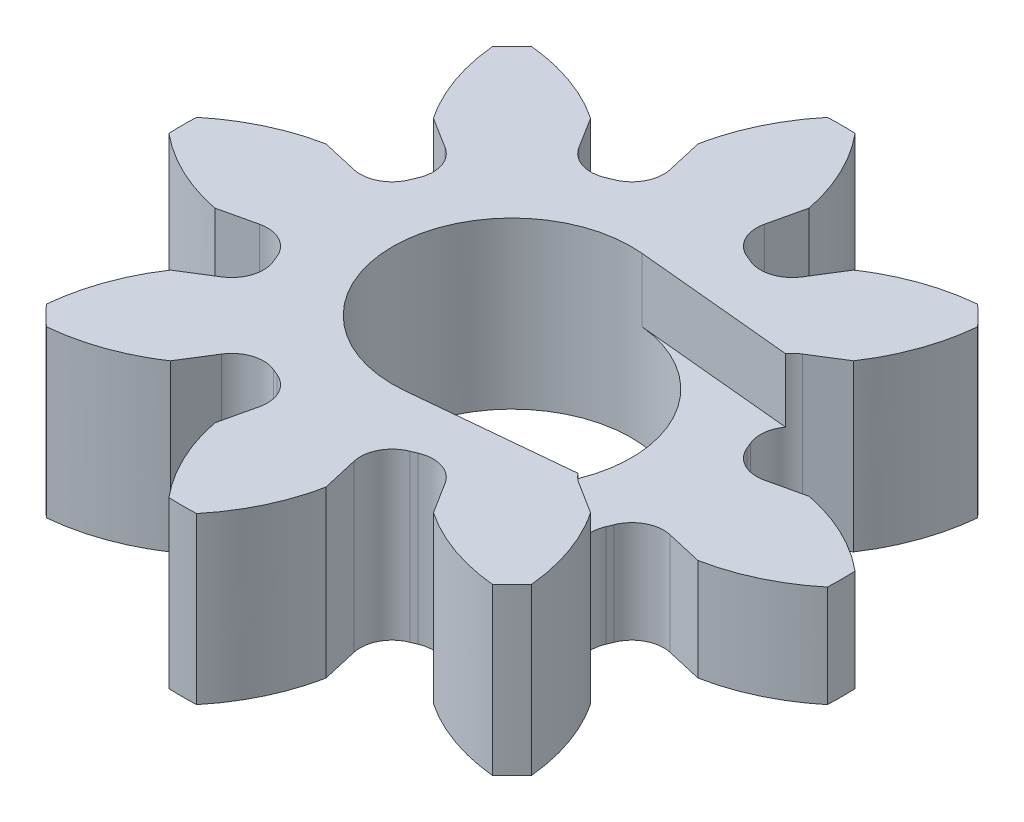
SolidWorks part; units mm, degrees
ref_plane "Front Plane" through (0, 0, 0) normal (0, 0, 1) x (1, 0, 0)
ref_plane "Top Plane" through (0, 0, 0) normal (0, 1, 0) x (1, 0, 0)
ref_plane "Right Plane" through (0, 0, 0) normal (1, 0, 0) x (0, 0, -1)
sketch "Sketch1" plane through (0, 0, 0) normal (0, 1, 0) x (1, 0, 0)
  circle A0 centre (0, 0) radius 8.283 construction
  circle A1 centre (0, 0) radius 5.6945
  circle A2 centre (0, 0) radius 3.75
  dimension "D1" = 16.566
  dimension "D2" = 11.389
  dimension "D3" = 7.5
extrude "Boss-Extrude1" add sketch "Sketch1" along normal blind 5.2
sketch "Sketch2" plane through (0, 5.2, 0) normal (0, 1, 0) x (1, 0, 0)
  line L0 (0, 0) -> (1.7453, 7.5853) construction
  line L1 (0, 0) -> (-4.624, 6.2611) construction
  line L2 (0, 0) -> (-7.7631, 0.5631) construction
  line L3 (0, 0) -> (-5.4792, -5.5282) construction
  line L4 (0, 0) -> (0.6323, -7.7578) construction
  line L5 (0, 0) -> (6.3021, -4.568) construction
  line L6 (6.3021, -4.568) -> (0.6323, -7.7578) construction
  line L7 (0.6323, -7.7578) -> (-5.4792, -5.5282) construction
  line L8 (-5.4792, -5.5282) -> (-7.7631, 0.5631) construction
  line L9 (-7.7631, 0.5631) -> (-4.624, 6.2611) construction
  line L10 (-4.624, 6.2611) -> (1.7453, 7.5853) construction
  line L11 (-4.624, 6.2611) -> (0.609, 10.1259) construction
  line L12 (-7.7631, 0.5631) -> (-6.8218, 13.5399) construction
  line L13 (-5.4792, -5.5282) -> (-19.3407, 8.2103) construction
  line L14 (0.6323, -7.7578) -> (-25.3035, -9.8716) construction
  line L15 (6.3021, -4.568) -> (-12.7878, -30.9043) construction
  line L16 (0, 0) -> (0, 10.3537) construction
  line L17 (0, 0) -> (1.6159, 8.1238) construction
  line L18 (1.2769, 5.5495) -> (1.7453, 7.5853)
  line L19 (-1.2769, 5.5495) -> (-1.7453, 7.5853)
  line L20 (3.0212, 4.827) -> (4.1295, 6.5977)
  line L21 (4.827, 3.0212) -> (6.5977, 4.1295)
  line L22 (5.5495, 1.2769) -> (7.5853, 1.7453)
  line L23 (5.5495, -1.2769) -> (7.5853, -1.7453)
  line L24 (4.827, -3.0212) -> (6.5977, -4.1295)
  line L25 (3.0212, -4.827) -> (4.1295, -6.5977)
  line L26 (1.2769, -5.5495) -> (1.7453, -7.5853)
  line L27 (-1.2769, -5.5495) -> (-1.7453, -7.5853)
  line L28 (-3.0212, -4.827) -> (-4.1295, -6.5977)
  line L29 (-4.827, -3.0212) -> (-6.5977, -4.1295)
  line L30 (-5.5495, -1.2769) -> (-7.5853, -1.7453)
  line L31 (-5.5495, 1.2769) -> (-7.5853, 1.7453)
  line L32 (-4.827, 3.0212) -> (-6.5977, 4.1295)
  line L33 (-3.0212, 4.827) -> (-4.1295, 6.5977)
  line L34 (0, 0) -> (1.2769, 5.5495) construction
  line L35 (0, 0) -> (4.827, 3.0212) construction
  circle A0 centre (0, 0) radius 7.7835 construction
  circle A1 centre (0, 0) radius 8.283 construction
  arc A2 (0.4355, 10.3446) -> (2.295, -10.0962) centre (0, 0) ccw construction
  circle A3 centre (0, 0) radius 5.6945 construction
  arc A4 (0.4355, 10.3446) -> (-0.4355, 10.3446) centre (0, 0) ccw
  arc A5 (1.2769, 5.5495) -> (-1.2769, 5.5495) centre (0, 0) ccw
  arc A6 (7.6227, 7.0068) -> (7.0068, 7.6227) centre (0, 0) ccw
  arc A7 (4.827, 3.0212) -> (3.0212, 4.827) centre (0, 0) ccw
  arc A8 (10.3446, -0.4355) -> (10.3446, 0.4355) centre (0, 0) ccw
  arc A9 (5.5495, -1.2769) -> (5.5495, 1.2769) centre (0, 0) ccw
  arc A10 (7.0068, -7.6227) -> (7.6227, -7.0068) centre (0, 0) ccw
  arc A11 (3.0212, -4.827) -> (4.827, -3.0212) centre (0, 0) ccw
  arc A12 (-0.4355, -10.3446) -> (0.4355, -10.3446) centre (0, 0) ccw
  arc A13 (-1.2769, -5.5495) -> (1.2769, -5.5495) centre (0, 0) ccw
  arc A14 (-7.6227, -7.0068) -> (-7.0068, -7.6227) centre (0, 0) ccw
  arc A15 (-4.827, -3.0212) -> (-3.0212, -4.827) centre (0, 0) ccw
  arc A16 (-10.3446, 0.4355) -> (-10.3446, -0.4355) centre (0, 0) ccw
  arc A17 (-5.5495, 1.2769) -> (-5.5495, -1.2769) centre (0, 0) ccw
  arc A18 (-7.0068, 7.6227) -> (-7.6227, 7.0068) centre (0, 0) ccw
  arc A19 (-3.0212, 4.827) -> (-4.827, 3.0212) centre (0, 0) ccw
  spline S0 degree 3 poles (1.7453, 7.5853) (1.0051, 11.4003) (-7.931, 15.6707) (-30.6497, 4.2431) (-26.2946, -23.903) (-12.7878, -30.9043) knots 0 0 0 0 0.160993 0.360844 1 1 1 1 construction
  spline S1 degree 3 poles (1.7453, 7.5853) (1.5544, 8.5898) (1.0898, 9.5579) (0.4355, 10.3446) knots 0 0 0 0 1 1 1 1
  spline S2 degree 3 poles (6.5977, 4.1295) (7.173, 4.9747) (7.5291, 5.9879) (7.6227, 7.0068) knots 0 0 0 0 1 1 1 1
  spline S3 degree 3 poles (-1.7453, 7.5853) (-1.5544, 8.5898) (-1.0898, 9.5579) (-0.4355, 10.3446) knots 0 0 0 0 1 1 1 1
  spline S4 degree 3 poles (4.1295, 6.5977) (4.9747, 7.173) (5.9879, 7.5291) (7.0068, 7.6227) knots 0 0 0 0 1 1 1 1
  spline S5 degree 3 poles (7.5853, -1.7453) (8.5898, -1.5544) (9.5579, -1.0898) (10.3446, -0.4355) knots 0 0 0 0 1 1 1 1
  spline S6 degree 3 poles (7.5853, 1.7453) (8.5898, 1.5544) (9.5579, 1.0898) (10.3446, 0.4355) knots 0 0 0 0 1 1 1 1
  spline S7 degree 3 poles (4.1295, -6.5977) (4.9747, -7.173) (5.9879, -7.5291) (7.0068, -7.6227) knots 0 0 0 0 1 1 1 1
  spline S8 degree 3 poles (6.5977, -4.1295) (7.173, -4.9747) (7.5291, -5.9879) (7.6227, -7.0068) knots 0 0 0 0 1 1 1 1
  spline S9 degree 3 poles (-1.7453, -7.5853) (-1.5544, -8.5898) (-1.0898, -9.5579) (-0.4355, -10.3446) knots 0 0 0 0 1 1 1 1
  spline S10 degree 3 poles (1.7453, -7.5853) (1.5544, -8.5898) (1.0898, -9.5579) (0.4355, -10.3446) knots 0 0 0 0 1 1 1 1
  spline S11 degree 3 poles (-6.5977, -4.1295) (-7.173, -4.9747) (-7.5291, -5.9879) (-7.6227, -7.0068) knots 0 0 0 0 1 1 1 1
  spline S12 degree 3 poles (-4.1295, -6.5977) (-4.9747, -7.173) (-5.9879, -7.5291) (-7.0068, -7.6227) knots 0 0 0 0 1 1 1 1
  spline S13 degree 3 poles (-7.5853, 1.7453) (-8.5898, 1.5544) (-9.5579, 1.0898) (-10.3446, 0.4355) knots 0 0 0 0 1 1 1 1
  spline S14 degree 3 poles (-7.5853, -1.7453) (-8.5898, -1.5544) (-9.5579, -1.0898) (-10.3446, -0.4355) knots 0 0 0 0 1 1 1 1
  spline S15 degree 3 poles (-4.1295, 6.5977) (-4.9747, 7.173) (-5.9879, 7.5291) (-7.0068, 7.6227) knots 0 0 0 0 1 1 1 1
  spline S16 degree 3 poles (-6.5977, 4.1295) (-7.173, 4.9747) (-7.5291, 5.9879) (-7.6227, 7.0068) knots 0 0 0 0 1 1 1 1
  dimension "D1" = 16.566
  dimension "D2" = 15.567
  dimension "D3" = 20.7075
  dimension "D4" = 6.5055
  dimension "D6" = 19.5164
  dimension "D7" = 26.0218
  dimension "D8" = 32.5273
  dimension "D5" = 13.0109
  dimension "D9" = 11.25
  dimension "D10" = 49.404
  dimension "D12" = 45
  dimension "D11" = 8
extrude "Boss-Extrude3" add sketch "Sketch2" against normal blind 5.2
fillet "Fillet1" radius 1 2 edges at (1.2769, 2.6, -5.5495) (-1.2769, 2.6, -5.5495)
fillet "Fillet2" radius 1 14 edges at (-5.5495, 2.6, 1.2769) (-4.827, 2.6, 3.0212) (-3.0212, 2.6, 4.827) (-1.2769, 2.6, 5.5495) (1.2769, 2.6, 5.5495) (3.0212, 2.6, 4.827) (4.827, 2.6, 3.0212) (5.5495, 2.6, 1.2769) (5.5495, 2.6, -1.2769) (4.827, 2.6, -3.0212) (-4.827, 2.6, -3.0212) (-5.5495, 2.6, -1.2769) (3.0212, 2.6, -4.827) (-3.0212, 2.6, -4.827)
sketch "Sketch3" plane through (0, 5.2, 0) normal (0, 1, 0) x (1, 0, 0)
  line L0 (0, 0) -> (14.2, 0) construction
  line L1 (0.3565, 3.733) -> (14.4282, 2.3891)
  line L2 (0.3565, -3.733) -> (14.4282, -2.3891)
  arc A0 (14.4282, 2.3891) -> (14.4282, -2.3891) centre (14.2, 0) ccw
  circle A1 centre (0, 0) radius 3.75 construction
  arc A2 (0.3565, -3.733) -> (0.3565, 3.733) centre (0, 0) ccw
  dimension "D2" = 4.8
  dimension "D1" = 14.2
extrude "Cut-Extrude1" cut sketch "Sketch3" against normal blind 2
equation "\"value\" = 6.505453"
equation "\"D4@Sketch2\"=\"value\""
equation "\"D6@Sketch2\"=\"value\"*3"
equation "\"D7@Sketch2\"=\"value\"*4"
equation "\"D8@Sketch2\"=\"value\"*5"
equation "\"D5@Sketch2\"=\"value\"*2"
